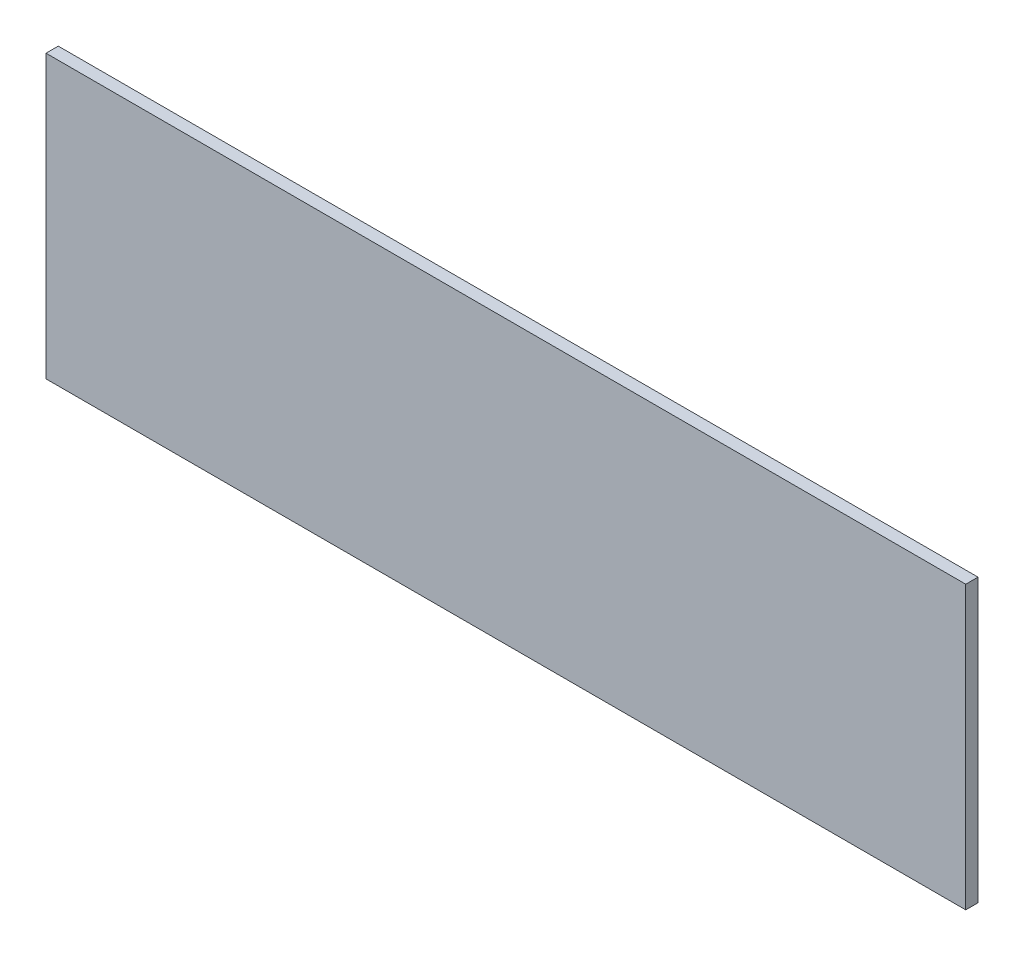
SolidWorks part; units mm, degrees
material "Pine"
ref_plane "Front Plane" through (0, 0, 0) normal (0, 0, 1) x (1, 0, 0)
ref_plane "Top Plane" through (0, 0, 0) normal (0, 1, 0) x (1, 0, 0)
ref_plane "Right Plane" through (0, 0, 0) normal (1, 0, 0) x (0, 0, -1)
sketch "Sketch1" plane through (0, 0, 0) normal (0, 0, 1) x (1, 0, 0)
  line L6 (0, 0) -> (900, 0)
  line L10 (0, 0) -> (0, 276)
  line L11 (0, 276) -> (900, 276)
  line L12 (900, 0) -> (900, 276)
  dimension "D2" = 900
  dimension "D3" = 276
extrude "Boss-Extrude1" add sketch "Sketch1" along normal blind 12
